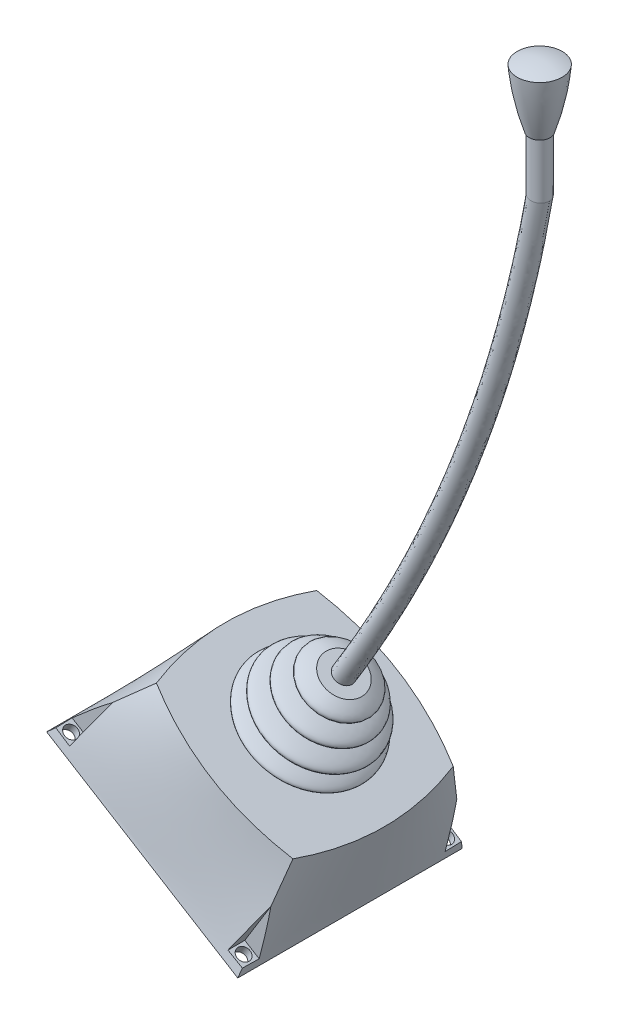
SolidWorks part; units mm, degrees
material "ABS"
ref_plane "Front Plane" through (0, 0, 0) normal (0, 0, 1) x (1, 0, 0)
ref_plane "Top Plane" through (0, 0, 0) normal (0, 1, 0) x (1, 0, 0)
ref_plane "Right Plane" through (0, 0, 0) normal (1, 0, 0) x (0, 0, -1)
sketch "Sketch1" plane through (0, 0, 0) normal (0, 0, 1) x (1, 0, 0)
  line L0 (0, 25.7312) -> (0, -89.3847)
  line L1 (0, -194.2439) -> (0, 194.2439) construction
  spline S0 degree 2 poles (0, -89.3847) (-76.6193, -517.8162) (-305.2823, -889.3847) knots 0 0 0 1 1 1
  dimension "D1" = 800
ref_plane "Plane1" through (0, 25.7312, 0) normal (0, 1, 0) x (1, 0, 0)
sketch "Sketch2" plane through (0, 25.7312, 0) normal (0, 1, 0) x (1, 0, 0)
  circle A0 centre (0, 0) radius 15
  dimension "D1" = 30
sweep "Sweep1" add profiles "Sketch2" path "Sketch1"
sketch "Sketch4" plane through (0, 0, 0) normal (0, 0, 1) x (1, 0, 0)
  line L3 (0, 92.5628) -> (0, -4.258)
  line L4 (0, -4.258) -> (16.4963, -4.258)
  line L5 (0, 92.5628) -> (0, -4.258)
  spline S0 degree 2 poles (16.4963, -4.258) (31.0658, 40.1067) (35, 86.6021) knots 0 0 0 1 1 1
  spline S2 degree 2 poles (0, 92.5628) (17.5, 92.5628) (35, 86.6021) knots 0.5 0.5 0.5 1 1 1
  dimension "D1" = 35
revolve "Revolve3" add sketch "Sketch4" angle 360 about L3
sketch "Sketch6" plane through (0, 0, 0) normal (0, 0, 1) x (1, 0, 0)
  line L0 (-305.2823, -889.3847) -> (-277.6757, -906.3738)
  line L1 (-318.0571, -881.5231) -> (-292.5075, -897.2463) construction
  line L2 (-305.2823, -889.3847) -> (-366.2988, -988.5341)
  line L3 (-366.2988, -988.5341) -> (-331.6632, -1009.8488)
  spline S0 degree 2 poles (-277.6757, -906.3738) (-249.0709, -940.1476) (-289.1993, -930.6906) knots 0 0 0 1 1 1
  spline S1 degree 2 poles (-289.1993, -930.6906) (-239.6489, -972.6708) (-293.8149, -963.2308) knots 0 0 0 1 1 1
  spline S2 degree 2 poles (-293.8149, -963.2308) (-242.5911, -1007.1073) (-294.9688, -997.3866) knots 0 0 0 1 1 1
  spline S3 degree 3 poles (-294.9688, -997.3866) (-243.1052, -1051.2884) (-318.3705, -1013.7149) (-331.6632, -1009.8488) knots 0 0 0 0 1 1 1 1
revolve "Revolve4" add sketch "Sketch6" angle 360 about L2
sketch "Sketch7" plane through (-541.8566, -880.4959, 0) normal (-0.5241, -0.8517, 0) x (0.8517, -0.5241, 0)
  line L0 (331.1378, 125) -> (81.1378, -125) construction
  line L1 (81.1378, 125) -> (331.1378, 125) construction
  line L2 (81.1378, 125) -> (81.1378, -125) construction
  line L3 (81.1378, -125) -> (331.1378, -125) construction
  line L4 (331.1378, 125) -> (331.1378, -125) construction
  circle A0 centre (206.1378, 0) radius 40.6687 construction
  spline S0 degree 2 poles (81.1378, 125) (206.1378, 165.8324) (331.1378, 125) knots 0 0 0 1 1 1
  spline S1 degree 2 poles (331.1378, 125) (371.9702, 0) (331.1378, -125) knots 0 0 0 1 1 1
  spline S2 degree 2 poles (331.1378, -125) (206.1378, -165.8324) (81.1378, -125) knots 0 0 0 1 1 1
  spline S3 degree 2 poles (81.1378, -125) (40.3054, 0) (81.1378, 125) knots 0 0 0 1 1 1
  point P4 (206.1378, 0)
  point P20 (206.1378, 0)
  point P21 (206.1378, 0)
  point P22 (206.1378, 0)
  point P23 (206.1378, 0)
  dimension "D1" = 250
ref_plane "Plane2" through (-620.4726, -1008.2438, 0) normal (-0.5241, -0.8517, 0) x (-0.8517, 0.5241, 0)
sketch "Sketch9" plane through (-620.4726, -1008.2438, 0) normal (-0.5241, -0.8517, 0) x (-0.8517, 0.5241, 0)
  line L0 (-31.1378, 175) -> (-381.1378, -175) construction
  line L1 (-381.1378, 175) -> (-31.1378, 175)
  line L2 (-381.1378, 175) -> (-381.1378, -175)
  line L3 (-381.1378, -175) -> (-31.1378, -175)
  line L4 (-31.1378, 175) -> (-31.1378, -175)
  point P4 (-206.1378, 0)
  dimension "D1" = 350
loft "Loft1" add profiles "Sketch9", "Sketch7"
sketch "Sketch10" plane through (-541.8566, -880.4959, 0) normal (0.5241, 0.8517, 0) x (0.8517, -0.5241, 0)
  line L0 (31.1378, 175) -> (381.1378, 175) construction
  line L1 (351.1378, 175) -> (381.1378, 175)
  line L2 (351.1378, 175) -> (351.1378, 145)
  line L3 (351.1378, 145) -> (381.1378, 145)
  line L4 (381.1378, 175) -> (381.1378, 145)
  line L5 (381.1378, 175) -> (381.1378, -175) construction
  line L6 (61.1378, 145) -> (61.1378, 175)
  line L7 (31.1378, 175) -> (61.1378, 175)
  line L8 (31.1378, 145) -> (31.1378, 175)
  line L9 (31.1378, 145) -> (61.1378, 145)
  line L10 (61.1378, -145) -> (31.1378, -145)
  line L11 (31.1378, -175) -> (31.1378, -145)
  line L12 (61.1378, -175) -> (31.1378, -175)
  line L13 (61.1378, -175) -> (61.1378, -145)
  line L14 (351.1378, -145) -> (351.1378, -175)
  line L15 (381.1378, -175) -> (351.1378, -175)
  line L16 (381.1378, -145) -> (381.1378, -175)
  line L17 (381.1378, -145) -> (351.1378, -145)
  point P23 (206.1378, 0)
  dimension "D1" = 30
  dimension "D2" = 4
extrude "Cut-Extrude1" cut sketch "Sketch10" against normal blind 137.5
ref_point "Point1"
hole_wizard "Hole1" positions "Sketch11" profile "Sketch12" legacy
sketch "Sketch11" plane through (-613.9213, -997.5982, 0) normal (0.5241, 0.8517, 0) x (0.8517, -0.5241, 0)
  point P0 (364.1369, -157.9991)
sketch "Sketch12" plane through (-303.803, -1188.4447, 157.9991) normal (0, 0, 1) x (-0.8517, 0.5241, 0)
  line L0 (0, 0) -> (0, 100)
  line L1 (0, 100) -> (10, 100)
  line L2 (10, 100) -> (10, 0)
  line L3 (10, 0) -> (0, 0)
  line L4 (0, 110) -> (0, -10) construction
  dimension "Diameter" = 20
  dimension "Depth" = 100
pattern_circular "CirPattern2" count 4 every 90 about axis through (175.5578, -108.0382, 0) along (0.5241, 0.8517, 0) of "Hole1"
scale "Scale2" bodies to scale 104 110 scale about origin uniform scaling yes scale factor 0.7
